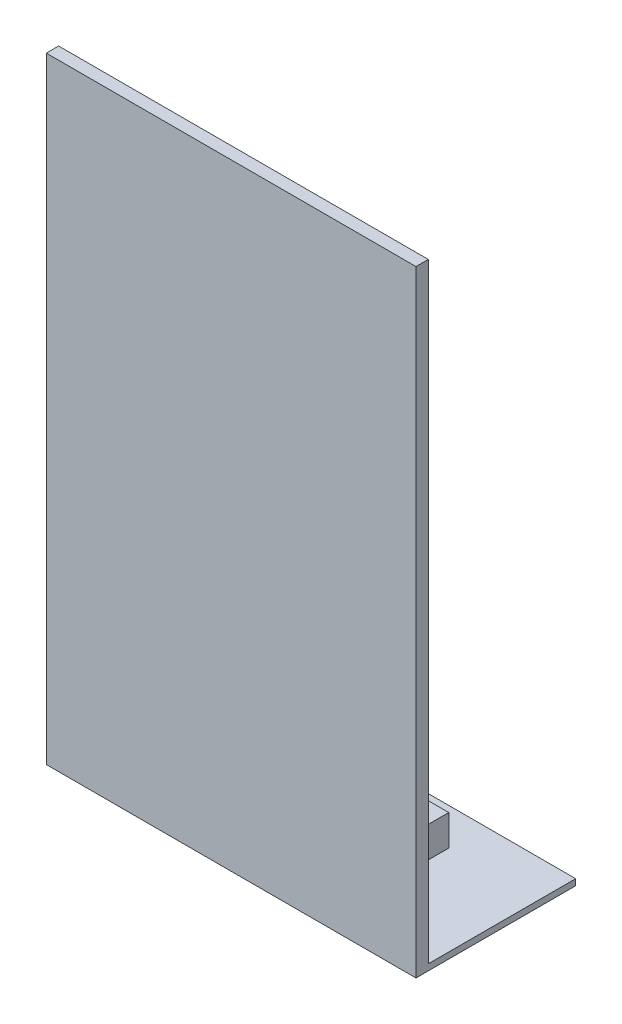
SolidWorks part; units mm, degrees
ref_plane "Front Plane" through (0, 0, 0) normal (0, 0, 1) x (1, 0, 0)
ref_plane "Top Plane" through (0, 0, 0) normal (0, 1, 0) x (1, 0, 0)
ref_plane "Right Plane" through (0, 0, 0) normal (1, 0, 0) x (0, 0, -1)
ref_plane "PL_TagFace" through (0, 0, 295.6) normal (0, 0, 1) x (1, 0, 0)
ref_plane "PL_DockBaseTop" through (0, 5, 0) normal (0, 1, 0) x (1, 0, 0)
sketch "SK_DockBase" plane through (0, 0, 0) normal (0, 1, 0) x (1, 0, 0)
  line L1 (-150, -176) -> (150, -176)
  line L2 (-150, -176) -> (-150, -305.6)
  line L3 (-150, -305.6) -> (150, -305.6)
  line L4 (150, -176) -> (150, -305.6)
  dimension "D1" = 129.6
  dimension "D2" = 300
  dimension "D3" = 176
  dimension "D4" = 150
extrude "EX_DockBase" add sketch "SK_DockBase" along normal blind 5
sketch "SK_DockWall" plane through (0, 0, 0) normal (0, 1, 0) x (1, 0, 0)
  line L1 (-150, -295.6) -> (150, -295.6)
  line L2 (-150, -295.6) -> (-150, -305.6)
  line L3 (-150, -305.6) -> (150, -305.6)
  line L4 (150, -295.6) -> (150, -305.6)
  dimension "D2" = 300
  dimension "D4" = 150
  dimension "D1" = 10
  dimension "D3" = 295.6
extrude "EX_DockWall" add sketch "SK_DockWall" along normal blind 500
sketch "SK_AprilTag" plane through (0, 0, 295.6) normal (0, 0, 1) x (1, 0, 0)
  line L1 (-40, 360) -> (40, 360)
  line L2 (-40, 360) -> (-40, 440)
  line L3 (-40, 440) -> (40, 440)
  line L4 (40, 360) -> (40, 440)
  dimension "D1" = 80
  dimension "D2" = 80
  dimension "D3" = 40
  dimension "D4" = 360
extrude "EX_AprilTag" add sketch "SK_AprilTag" against normal blind 1
sketch "SK_DockContacts" plane through (0, 5, 0) normal (0, 1, 0) x (1, 0, 0)
  line L1 (51, -206) -> (77, -206)
  line L2 (51, -206) -> (51, -226)
  line L3 (51, -226) -> (77, -226)
  line L4 (77, -206) -> (77, -226)
  line L6 (-51, -206) -> (-77, -206)
  line L7 (-51, -206) -> (-51, -226)
  line L8 (-51, -226) -> (-77, -226)
  line L9 (-77, -206) -> (-77, -226)
  dimension "D1" = 20
  dimension "D2" = 26
  dimension "D3" = 206
  dimension "D4" = 51
  dimension "D5" = 20
  dimension "D6" = 26
  dimension "D7" = 206
  dimension "D8" = 51
extrude "EX_DockContacts" add sketch "SK_DockContacts" along normal blind 25
equation "\"BODY_L\"= 420"
equation "\"BODY_W\"= 340"
equation "\"FLOOR_Z\"= 35"
equation "\"DECK_Z\"= 180"
equation "\"DECK_T\"= 2"
equation "\"GRID\"= 20"
equation "\"PROFILE\"= 20"
equation "\"SM_T\"= 1.5"
equation "\"PAN_T\"= 1.5"
equation "\"PAN_TOP\"= \"FLOOR_Z\" + \"PAN_T\""
equation "\"RAIL_Y\"= 140"
equation "\"RAIL_X\"= \"BODY_L\" / 2 - \"PROFILE\" / 2 - 2"
equation "\"BOTRING_Z\"= \"PAN_TOP\" + \"PROFILE\" / 2"
equation "\"TOPRING_Z\"= \"DECK_Z\" - \"DECK_T\" - \"PROFILE\" / 2"
equation "\"DRAWER_Z\"= 93"
equation "\"MIDX_Z\"= \"DRAWER_Z\" - \"SM_T\" - \"PROFILE\" / 2"
equation "\"SKIN_Y\"= \"RAIL_Y\" + \"PROFILE\" / 2"
equation "\"SKIN_T\"= 2"
equation "\"WHEEL_D\"= 144"
equation "\"WHEEL_W\"= 52"
equation "\"TRACK\"= 365"
equation "\"AXLE_Z\"= \"WHEEL_D\" / 2"
equation "\"WHEEL_WEB_OFF\"= 6"
equation "\"HUB_T\"= 8"
equation "\"BUSHING_L\"= 6"
equation "\"HUB_GAP\"= 1"
equation "\"MOTOR_UP\"= 7"
equation "\"MOTOR_FACE_Y\"= \"TRACK\" / 2 + \"WHEEL_WEB_OFF\" - (\"BUSHING_L\" + \"HUB_GAP\" + \"HUB_T\")"
equation "\"MOTOR_AXIS_Z\"= \"AXLE_Z\" + \"MOTOR_UP\""
equation "\"CASTER_D\"= 50"
equation "\"CASTER_X\"= 150"
equation "\"CASTER_H\"= 68"
equation "\"POST_X\"= -40"
equation "\"POST_DY\"= 120"
equation "\"POST_SIZE\"= 20"
equation "\"POST_TOP\"= 400"
equation "\"BRACE_Z\"= 335"
equation "\"STRUT_X0\"= -140"
equation "\"HEAD_X0\"= -110"
equation "\"HEAD_X1\"= 12"
equation "\"BEZEL_T\"= 3"
equation "\"WEDGE_MID\"= 7.7"
equation "\"OAK_D\"= 22.9"
equation "\"HEAD_W\"= 210"
equation "\"HEAD_Z0\"= \"POST_TOP\""
equation "\"HEAD_TOP\"= 525"
equation "\"HEAD_TOP_X\"= -20"
equation "\"SCREEN_ANG\"= 35"
equation "\"LENS_X\"= 45.6"
equation "\"LENS_Z\"= 450"
equation "\"OAK_TILT\"= 5"
equation "\"OAK_VFOV_DEPTH\"= 79.5"
equation "\"OAK_VFOV_RGB\"= 72"
equation "\"LIDAR_X\"= 110"
equation "\"SCAN_Z\"= 260"
equation "\"STRUT_Z\"= \"SCAN_Z\" - 20"
equation "\"LIDAR_SCAN_H\"= 27.2"
equation "\"LIDAR_MOUNT_Z\"= \"SCAN_Z\" - \"LIDAR_SCAN_H\""
equation "\"ESTOP_X\"= -172.5"
equation "\"ESTOP_Y\"= -127.5"
equation "\"ESTOP_TOP\"= 225"
equation "\"BUMPER_T\"= 15"
equation "\"BUMPER_Z0\"= 40"
equation "\"BUMPER_Z1\"= 130"
equation "\"CLIFF_X\"= 218"
equation "\"CLIFF_Y\"= 105"
equation "\"CLIFF_Z\"= 72"
equation "\"CLIFF_ANG\"= 50"
equation "\"CONTACT_X\"= 216"
equation "\"CONTACT_Y\"= 64"
equation "\"CONTACT_Z\"= 30"
equation "\"DOCK_TAG_DIST\"= 250"
equation "\"DOCK_TAG_SIZE\"= 80"
equation "\"DOCK_TAG_Z\"= 400"
equation "\"BAT_L\"= 240"
equation "\"BAT_W\"= 90"
equation "\"BAT_H\"= 58"
equation "\"BAT_Z\"= \"DRAWER_Z\" + \"SM_T\""
equation "\"BAT_X\"= 0"
equation "\"PCB_L\"= 95"
equation "\"PCB_W\"= 120"
equation "\"PCB_H\"= 40"
equation "\"PCB_X\"= 62.5"
equation "\"DRV_X\"= 85"
equation "\"DRV_Y\"= 100"
equation "\"DRV_S\"= 50"
equation "\"COMPUTE_X\"= -65"
equation "\"COMPUTE_L\"= 90"
equation "\"COMPUTE_W\"= 160"
equation "\"D1@PL_TagFace\" = \"LENS_X\" + \"DOCK_TAG_DIST\""
equation "\"D1@SK_DockBase\" = \"LENS_X\" + \"DOCK_TAG_DIST\" + 10 - (\"CONTACT_X\" - 40)"
equation "\"D2@SK_DockBase\" = 300"
equation "\"D3@SK_DockBase\" = \"CONTACT_X\" - 40"
equation "\"D4@SK_DockBase\" = 150"
equation "\"D1@SK_DockWall\" = 10"
equation "\"D2@SK_DockWall\" = 300"
equation "\"D3@SK_DockWall\" = \"LENS_X\" + \"DOCK_TAG_DIST\""
equation "\"D4@SK_DockWall\" = 150"
equation "\"D1@SK_AprilTag\" = \"DOCK_TAG_SIZE\""
equation "\"D2@SK_AprilTag\" = \"DOCK_TAG_SIZE\""
equation "\"D3@SK_AprilTag\" = \"DOCK_TAG_SIZE\" / 2"
equation "\"D4@SK_AprilTag\" = \"DOCK_TAG_Z\" - \"DOCK_TAG_SIZE\" / 2"
equation "\"D1@SK_DockContacts\" = 20"
equation "\"D2@SK_DockContacts\" = 26"
equation "\"D3@SK_DockContacts\" = \"CONTACT_X\" - 10"
equation "\"D4@SK_DockContacts\" = \"CONTACT_Y\" - 13"
equation "\"D5@SK_DockContacts\" = 20"
equation "\"D6@SK_DockContacts\" = 26"
equation "\"D7@SK_DockContacts\" = \"CONTACT_X\" - 10"
equation "\"D8@SK_DockContacts\" = \"CONTACT_Y\" - 13"
equation "\"D1@EX_DockContacts\" = \"CONTACT_Z\" - 5"
